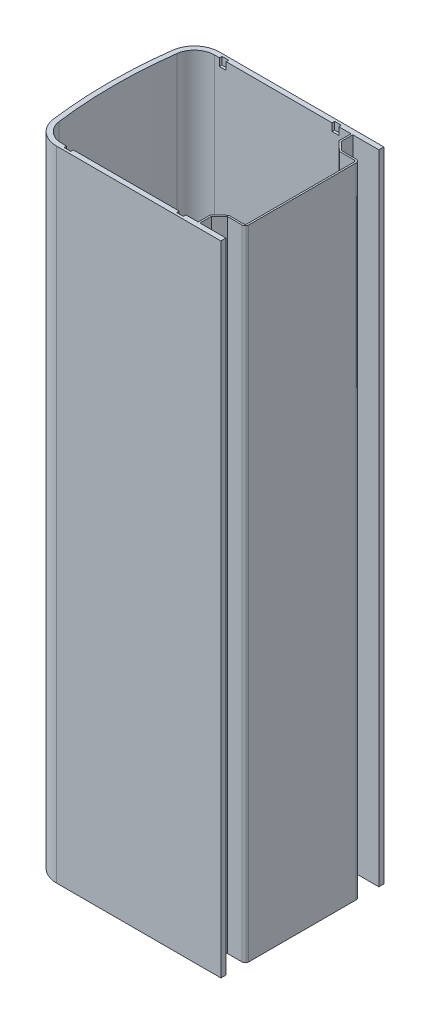
SolidWorks part; units mm, degrees
material "nhuapvc"
ref_plane "Front Plane" through (0, 0, 0) normal (0, 0, 1) x (1, 0, 0)
ref_plane "Top Plane" through (0, 0, 0) normal (0, 1, 0) x (1, 0, 0)
ref_plane "Right Plane" through (0, 0, 0) normal (1, 0, 0) x (0, 0, -1)
sketch "Sketch1" plane through (0, 0, 0) normal (0, 1, 0) x (1, 0, 0)
  line L1 (0, 48.5) -> (-97.8328, 48.5)
  line L3 (0, -48.5) -> (-97.8328, -48.5)
  line L5 (0, 0) -> (-110.9872, -46.8076) construction
  line L6 (0, 0) -> (-110.9872, 46.8076) construction
  line L7 (0, 45.5) -> (-97.8328, 45.5)
  line L8 (0, -45.5) -> (-97.8328, -45.5)
  line L9 (0, 48.5) -> (0, 45.5)
  line L10 (0, -48.5) -> (0, -45.5)
  arc A0 (-112.7078, 35.4327) -> (-112.7078, -35.4327) centre (160, 0) ccw
  arc A1 (-97.8328, -48.5) -> (-112.7078, -35.4327) centre (-97.8328, -33.5) cw
  arc A2 (-97.8328, 48.5) -> (-112.7078, 35.4327) centre (-97.8328, 33.5) ccw
  arc A3 (-97.8328, 45.5) -> (-109.7328, 35.0462) centre (-97.8328, 33.5) ccw
  arc A4 (-109.7328, 35.0462) -> (-109.7328, -35.0462) centre (160, 0) ccw
  arc A5 (-97.8328, -45.5) -> (-109.7328, -35.0462) centre (-97.8328, -33.5) cw
  point P0 (0, 0)
  dimension "D2" = 550
  dimension "D3" = 15
  dimension "D1" = 97
  dimension "D4" = 3
extrude "Boss-Extrude1" add sketch "Sketch1" along normal blind 380
sketch "Sketch2" plane through (0, 0, -45.5) normal (0, 0, 1) x (1, 0, 0)
  line L0 (-97.8328, 380) -> (0, 380) construction
  line L1 (-94.8328, 384.5) -> (-90.8328, 384.5)
  line L2 (-94.8328, 384.5) -> (-94.8328, 375.5)
  line L3 (-94.8328, 375.5) -> (-90.8328, 375.5)
  line L4 (-90.8328, 384.5) -> (-90.8328, 375.5)
  line L5 (-94.8328, 384.5) -> (-90.8328, 375.5) construction
  line L6 (-94.8328, 375.5) -> (-90.8328, 384.5) construction
  line L7 (-97.8328, 380) -> (-97.8328, 0) construction
  line L8 (-27.8328, 384.5) -> (-23.8328, 384.5)
  line L9 (-27.8328, 384.5) -> (-27.8328, 375.5)
  line L10 (-27.8328, 375.5) -> (-23.8328, 375.5)
  line L11 (-23.8328, 384.5) -> (-23.8328, 375.5)
  line L12 (-27.8328, 384.5) -> (-23.8328, 375.5) construction
  line L13 (-27.8328, 375.5) -> (-23.8328, 384.5) construction
  point P0 (-92.8328, 380)
  point P7 (-25.8328, 380)
  dimension "D1" = 9
  dimension "D2" = 4
  dimension "D3" = 4
  dimension "D4" = 9
  dimension "D5" = 3
  dimension "D6" = 63
extrude "Cut-Extrude1" cut sketch "Sketch2" against normal blind 1.5
mirror "Mirror1" about plane through (0, 0, 0) normal (0, 0, 1) of "Cut-Extrude1"
sketch "Sketch3" plane through (0, 0, 0) normal (0, 1, 0) x (1, 0, 0)
  line L0 (-1, 0) -> (-65.0718, 0) construction
  line L1 (0, 0) -> (0, 31.9526)
  line L2 (-2, 33.9526) -> (-10.4903, 33.9526)
  line L3 (-10.4903, 33.9526) -> (-15.4976, 38.607)
  line L4 (-15.4976, 38.607) -> (-15.4976, 45.5)
  line L5 (-23.8328, 45.5) -> (0, 45.5) construction
  line L6 (-1, 0) -> (-1, 31.9526)
  line L7 (-2, 32.9526) -> (-10.8833, 32.9526)
  line L8 (-10.8833, 32.9526) -> (-16.4976, 38.1712)
  line L9 (-16.4976, 38.1712) -> (-16.4976, 45.5)
  line L10 (-16.4976, 45.5) -> (-15.4976, 45.5)
  line L12 (-16.4976, -45.5) -> (-15.4976, -45.5)
  line L13 (-16.4976, -38.1712) -> (-16.4976, -45.5)
  line L14 (-10.8833, -32.9526) -> (-16.4976, -38.1712)
  line L15 (-2, -32.9526) -> (-10.8833, -32.9526)
  line L16 (-1, 0) -> (-1, -31.9526)
  line L17 (-15.4976, -38.607) -> (-15.4976, -45.5)
  line L18 (-10.4903, -33.9526) -> (-15.4976, -38.607)
  line L19 (-2, -33.9526) -> (-10.4903, -33.9526)
  line L20 (0, 0) -> (0, -31.9526)
  arc A0 (0, 31.9526) -> (-2, 33.9526) centre (-2, 31.9526) ccw
  arc A1 (-1, 31.9526) -> (-2, 32.9526) centre (-2, 31.9526) ccw
  arc A2 (-1, -31.9526) -> (-2, -32.9526) centre (-2, -31.9526) cw
  arc A3 (0, -31.9526) -> (-2, -33.9526) centre (-2, -31.9526) cw
  dimension "D1" = 2
  dimension "D2" = 1
extrude "Boss-Extrude2" add sketch "Sketch3" along normal up to surface (380 mm away) up to face at (-64.2486, 380, 0)
